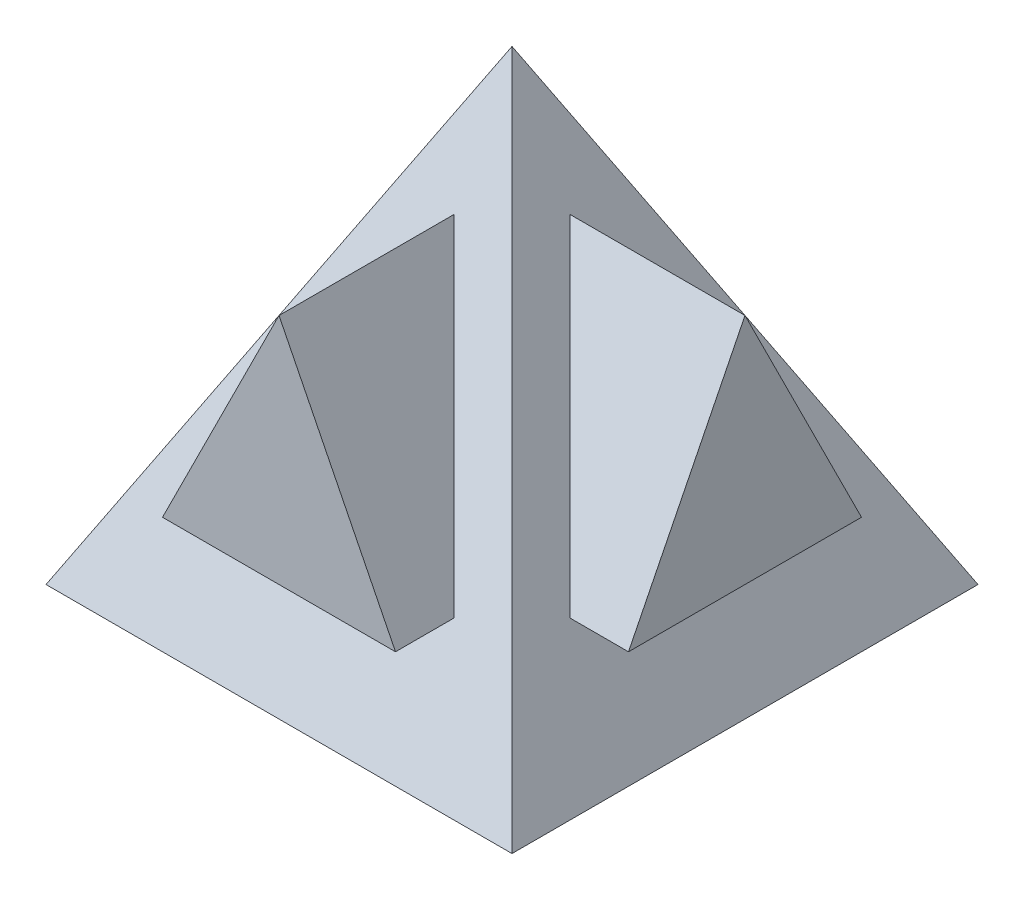
SolidWorks part; units mm, degrees
ref_plane "Front Plane" through (0, 0, 0) normal (0, 0, 1) x (1, 0, 0)
ref_plane "Top Plane" through (0, 0, 0) normal (0, 1, 0) x (1, 0, 0)
ref_plane "Right Plane" through (0, 0, 0) normal (1, 0, 0) x (0, 0, -1)
sketch "Sketch2" plane through (0, 0, 0) normal (0, 1, 0) x (1, 0, 0)
  line L1 (101.6, -101.6) -> (-101.6, -101.6)
  line L2 (101.6, -101.6) -> (101.6, 101.6)
  line L3 (101.6, 101.6) -> (-101.6, 101.6)
  line L4 (-101.6, -101.6) -> (-101.6, 101.6)
  line L5 (101.6, -101.6) -> (-101.6, 101.6) construction
  line L6 (101.6, 101.6) -> (-101.6, -101.6) construction
  point P0 (0, 0)
  dimension "D1" = 203.2
  dimension "D2" = 203.2
sketch "Sketch4" plane through (0, 0, 0) normal (0, 0, 1) x (1, 0, 0)
  point P0 (0, 203.2)
  dimension "D1" = 203.2
loft "Loft2" add profiles "Sketch4", "Sketch2"
sketch "Sketch5" plane through (0, 21.4524, 0) normal (0, 0, 1) x (1, 0, 0)
  line L0 (0, 130.9476) -> (-50.8, 29.3476)
  line L1 (-50.8, 29.3476) -> (50.8, 29.3476)
  line L2 (50.8, 29.3476) -> (0, 130.9476)
  line L5 (-101.6, -21.4524) -> (101.6, -21.4524) construction
  dimension "D1" = 101.6
  dimension "D2" = 50.8
  dimension "D3" = 101.6
  dimension "D4" = 50.8
extrude "Boss-Extrude1" add sketch "Sketch5" along normal blind 101.6 separate body
move or copy body "Body-Move/Copy2" bodies to move or copy 103 copy yes number of copies 1 rotation origin (0, 0, 0) rotation axis (0, 1, 0) rotation angle 90
combine bodies "Combine1" operation type add bodies to combine 101 103 105
